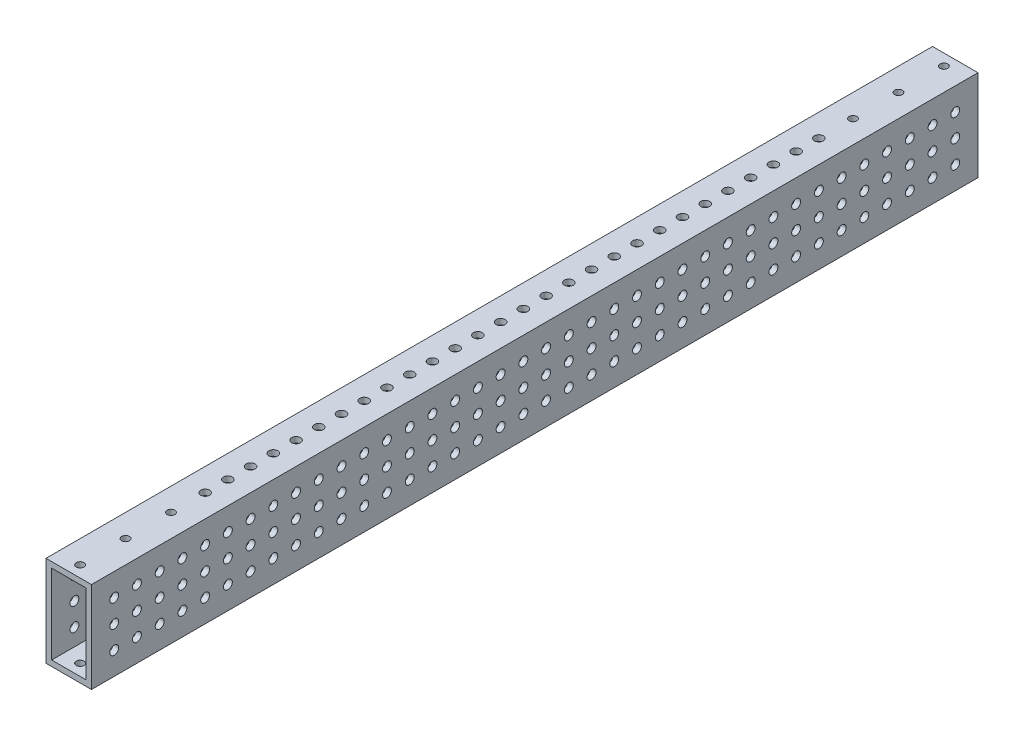
SolidWorks part; units mm, degrees
material "6061-T6 (SS)"
ref_plane "Front Plane" through (0, 0, 0) normal (0, 0, 1) x (1, 0, 0)
ref_plane "Top Plane" through (0, 0, 0) normal (0, 1, 0) x (1, 0, 0)
ref_plane "Right Plane" through (0, 0, 0) normal (1, 0, 0) x (0, 0, -1)
sketch "Sketch1" plane through (0, 0, 0) normal (0, 0, 1) x (1, 0, 0)
  line L0 (3.175, 3.175) -> (3.175, 47.625)
  line L1 (0, 0) -> (25.4, 0)
  line L2 (0, 0) -> (0, 50.8)
  line L3 (0, 50.8) -> (25.4, 50.8)
  line L4 (25.4, 0) -> (25.4, 50.8)
  line L5 (3.175, 47.625) -> (22.225, 47.625)
  line L6 (22.225, 3.175) -> (22.225, 47.625)
  line L7 (3.175, 3.175) -> (22.225, 3.175)
  dimension "D2" = 50.8
  dimension "D3" = 25.4
  dimension "D1" = 3.175
extrude "Boss-Extrude1" add sketch "Sketch1" along normal mid plane 495.3
sketch "Sketch2" plane through (0, 0, 0) normal (-1, 0, 0) x (0, 0, 1)
  line L0 (-234.95, 50.8) -> (-234.95, 0) construction
  line L1 (247.65, 50.8) -> (-247.65, 50.8) construction
  line L2 (247.65, 0) -> (-247.65, 0) construction
  line L3 (-247.65, 50.8) -> (-247.65, 0) construction
  circle A0 centre (-234.95, 38.1) radius 2.4892
  circle A1 centre (-234.95, 25.4) radius 2.4892
  circle A2 centre (-234.95, 12.7) radius 2.4892
  point P12 (-237.8088, 6.2346)
  point P13 (-237.8088, 20.8895)
  point P14 (0, 0)
  point P15 (-237.8088, 40.7093)
  dimension "D1" = 4.9784
  dimension "D2" = 12.7
  dimension "D3" = 12.7
  dimension "D4" = 12.7
  dimension "D5" = 12.7
extrude "Cut-Extrude1" cut sketch "Sketch2" against normal through all
pattern_linear "LPattern1" count 38 spacing 12.7 along (0, 0, 1) of "Cut-Extrude1"
sketch "Sketch3" plane through (0, 50.8, 0) normal (0, 1, 0) x (1, 0, 0)
  line L0 (12.7, 247.65) -> (12.7, -247.65) construction
  line L1 (25.4, 247.65) -> (0, 247.65) construction
  line L2 (25.4, -247.65) -> (0, -247.65) construction
  line L3 (25.4, 0) -> (0, 0) construction
  line L4 (25.4, -247.65) -> (25.4, 247.65) construction
  line L5 (0, -247.65) -> (0, 247.65) construction
  circle A0 centre (12.7, 234.95) radius 2.4892 construction
  circle A1 centre (12.7, 222.25) radius 2.4892 construction
  circle A2 centre (12.7, 209.55) radius 2.4892 construction
  circle A3 centre (12.7, 196.85) radius 2.4892 construction
  circle A4 centre (12.7, 184.15) radius 2.4892 construction
  circle A5 centre (12.7, 171.45) radius 2.4892
  circle A6 centre (12.7, 158.75) radius 2.4892
  circle A7 centre (12.7, 146.05) radius 2.4892
  circle A8 centre (12.7, 133.35) radius 2.4892
  circle A9 centre (12.7, 120.65) radius 2.4892
  circle A10 centre (12.7, 107.95) radius 2.4892
  circle A11 centre (12.7, 95.25) radius 2.4892
  circle A12 centre (12.7, 82.55) radius 2.4892
  circle A13 centre (12.7, 69.85) radius 2.4892
  circle A14 centre (12.7, 57.15) radius 2.4892
  circle A15 centre (12.7, 44.45) radius 2.4892
  circle A16 centre (12.7, 31.75) radius 2.4892
  circle A17 centre (12.7, 19.05) radius 2.4892
  circle A18 centre (12.7, 6.35) radius 2.4892
  circle A19 centre (12.7, -6.35) radius 2.4892
  circle A20 centre (12.7, -19.05) radius 2.4892
  circle A21 centre (12.7, -31.75) radius 2.4892
  circle A22 centre (12.7, -44.45) radius 2.4892
  circle A23 centre (12.7, -57.15) radius 2.4892
  circle A24 centre (12.7, -69.85) radius 2.4892
  circle A25 centre (12.7, -82.55) radius 2.4892
  circle A26 centre (12.7, -95.25) radius 2.4892
  circle A27 centre (12.7, -107.95) radius 2.4892
  circle A28 centre (12.7, -120.65) radius 2.4892
  circle A29 centre (12.7, -133.35) radius 2.4892
  circle A30 centre (12.7, -146.05) radius 2.4892
  circle A31 centre (12.7, -158.75) radius 2.4892
  circle A32 centre (12.7, -171.45) radius 2.4892
  circle A33 centre (12.7, -184.15) radius 2.4892 construction
  circle A34 centre (12.7, -196.85) radius 2.4892 construction
  circle A35 centre (12.7, -209.55) radius 2.4892 construction
  circle A36 centre (12.7, -222.25) radius 2.4892 construction
  circle A37 centre (12.7, -234.95) radius 2.4892 construction
  circle A38 centre (12.7, 241.3) radius 2.1526
  circle A40 centre (12.7, 215.9) radius 2.1526
  circle A41 centre (12.7, 190.5) radius 2.1526
  circle A42 centre (12.7, -241.3) radius 2.1526
  circle A43 centre (12.7, -215.9) radius 2.1526
  circle A44 centre (12.7, -190.5) radius 2.1526
  dimension "D1" = 4.9784
  dimension "D5" = 4.3053
  dimension "D2" = 12.7
  dimension "D4" = 12.7
  dimension "D6" = 6.35
  dimension "D8" = 25.4
  dimension "D3" = 38
  dimension "D7" = 3
extrude "Cut-Extrude2" cut sketch "Sketch3" against normal through all
hole_wizard "1/4-20 Tapped Hole1" positions "3DSketch1" profile "Sketch4" tap size "1/4-20" standard "ANSI Inch"
sketch3d "3DSketch1"
  line L0 (12.7, 0, -146.05) -> (12.7, 3.175, -146.05) construction
  line L1 (12.7, 0, 146.05) -> (12.7, 3.175, 146.05) construction
  line L2 (12.7, 0, -19.05) -> (12.7, 3.175, -19.05) construction
  line L3 (12.7, 0, 19.05) -> (12.7, 3.175, 19.05) construction
  point P0 (12.7, 0, -146.05)
  point P4 (12.7, 0, 146.05)
  point P8 (12.7, 0, -19.05)
  point P12 (12.7, 0, 19.05)
cosmetic thread "Hole Thread1" parameters "D2"=6.35
cosmetic thread "Hole Thread2" parameters "D2"=6.35
cosmetic thread "Hole Thread3" parameters "D2"=6.35
cosmetic thread "Hole Thread4" parameters "D2"=6.35
sketch "Sketch4" plane through (12.7, 0, -146.05) normal (1, 0, 0) x (0, 0, -1)
  line L0 (0, 0) -> (0, 4.7088)
  line L1 (0, 4.7088) -> (2.5527, 3.175)
  line L2 (2.5527, 3.175) -> (2.5527, 0)
  line L5 (2.5527, 0) -> (0, 0)
  line L10 (0, 4.7088) -> (-2.5527, 3.175) construction
  line L11 (0, -6.35) -> (0, 107.95) construction
  dimension "Tap Drill Dia." = 5.1054
  dimension "Tap Drill Depth" = 3.175
  dimension "Drill Angle" = 118
